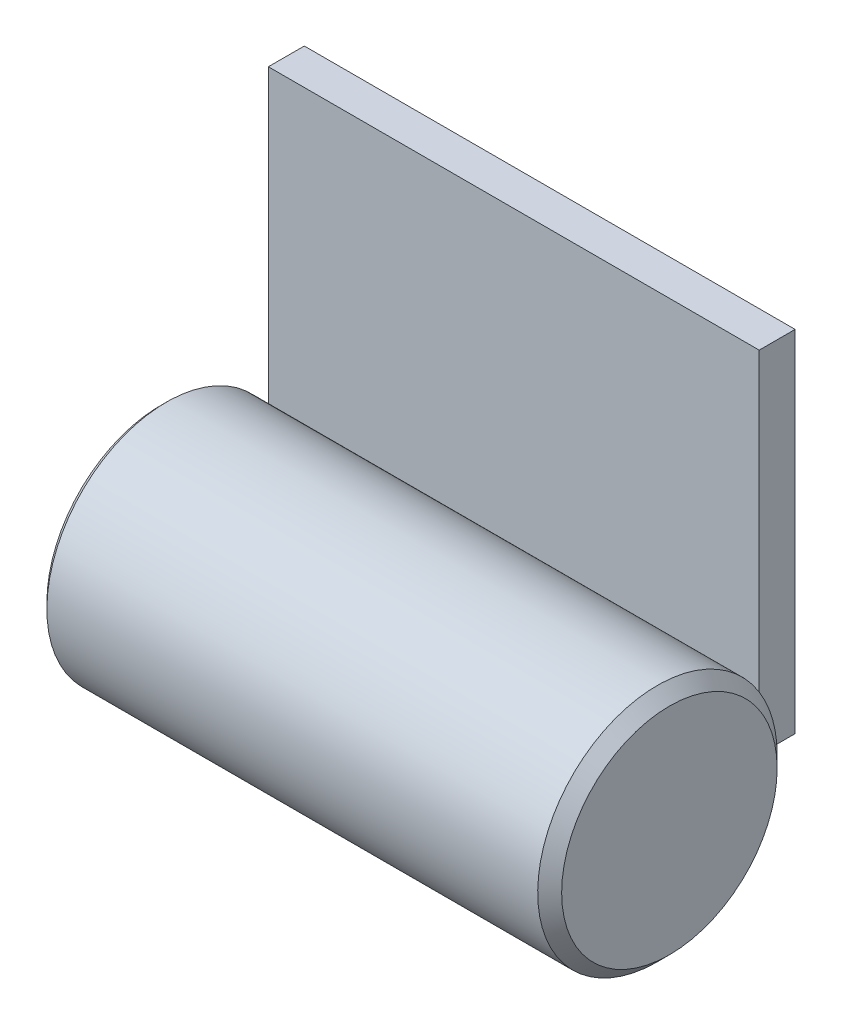
SolidWorks part; units mm, degrees
ref_plane "Спереди" through (0, 0, 0) normal (0, 0, 1) x (1, 0, 0)
ref_plane "Сверху" through (0, 0, 0) normal (0, 1, 0) x (1, 0, 0)
ref_plane "Справа" through (0, 0, 0) normal (1, 0, 0) x (0, 0, -1)
sketch "Эскиз1" plane through (0, 0, 0) normal (0, 1, 0) x (1, 0, 0)
  line L0 (92.6529, 0) -> (92.6529, 18)
  line L1 (90.6529, 20) -> (8.6529, 20)
  line L2 (7.6529, 19) -> (7.6529, 14.75)
  line L3 (7.6529, 14.75) -> (8.6529, 13.75)
  line L4 (76.7985, 0) -> (92.6529, 0)
  line L5 (102.994, 0) -> (-18.114, 0) construction
  line L6 (8.6529, 13.75) -> (71.6294, 13.75)
  line L7 (8.6529, 20) -> (7.6529, 19)
  line L8 (92.6529, 18) -> (90.6529, 20)
  line L9 (71.6294, 3.4302) -> (71.6294, 13.75)
  line L10 (71.6294, 3.4302) -> (76.7985, 0)
  point P1 (92.6529, 20)
  point P9 (7.6529, 20)
  point P10 (7.6529, 13.75)
  dimension "D1" = 1
  dimension "D2" = 45
  dimension "D3" = 1
  dimension "D4" = 45
  dimension "D5" = 2
  dimension "D6" = 45
  dimension "D7" = 6.25
revolve "Повернуть4" add sketch "Эскиз1" angle 360 about L5
sketch "Эскиз2" plane through (0, 0, 0) normal (0, 1, 0) x (1, 0, 0)
  line L0 (90.6529, 20) -> (90.6529, -20) construction
  line L6 (90.6529, 17.0037) -> (8.6529, 17.0037)
  line L7 (90.6529, 17.0037) -> (90.6529, 23.0049)
  line L8 (90.6529, 23.0049) -> (8.6529, 23.0049)
  line L9 (8.6529, 17.0037) -> (8.6529, 23.0049)
extrude "Бобышка-Вытянуть1" add sketch "Эскиз2" along normal blind 60
sketch "Эскиз3" plane through (0, 0, 0) normal (0, -1, 0) x (1, 0, 0)
  line L1 (90.6529, -23.0049) -> (8.6529, -23.0049)
  line L2 (90.6529, -23.0049) -> (90.6529, -20)
  line L3 (90.6529, -20) -> (8.6529, -20)
  line L4 (8.6529, -23.0049) -> (8.6529, -20)
extrude "Вырез-Вытянуть1" cut sketch "Эскиз3" against normal blind 1.5
